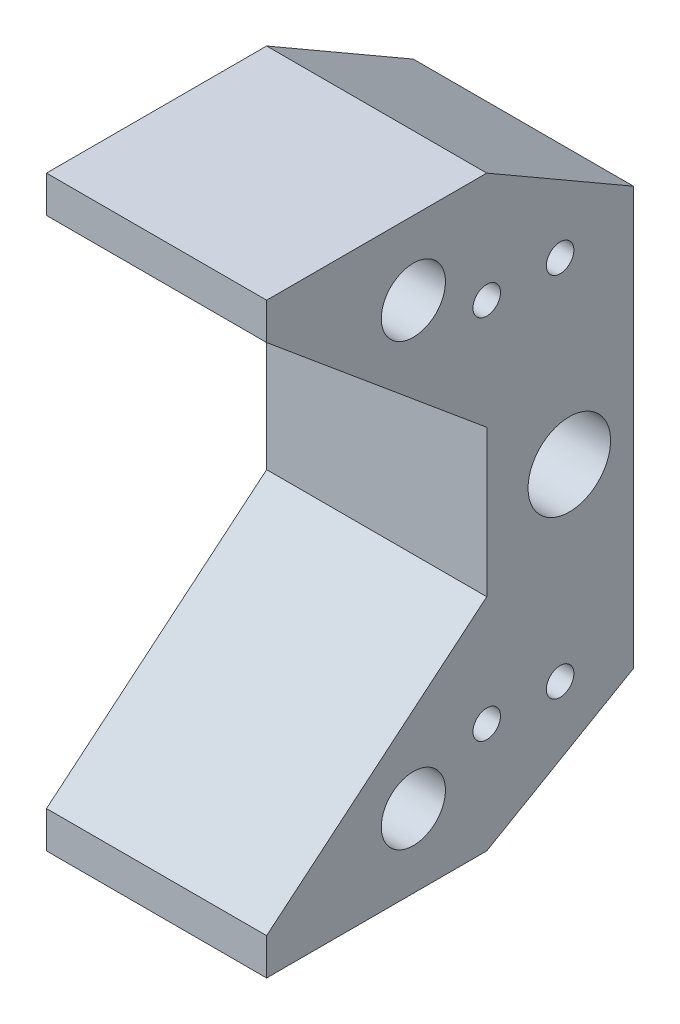
SolidWorks part; units mm, degrees
ref_plane "Front Plane" through (0, 0, 0) normal (1, 0, 0) x (0, 1, 0)
ref_plane "Top Plane" through (0, 0, 0) normal (0, 0, 1) x (0, 1, 0)
ref_plane "Right Plane" through (0, 0, 0) normal (0, 1, 0) x (-1, 0, 0)
sketch "Sketch1" plane through (0, 0, 0) normal (1, 0, 0) x (0, 1, 0)
  line L0 (0, 0) -> (-25.4, 0)
  line L1 (-25.4, 0) -> (-88.9, 76.2)
  line L2 (-88.9, 76.2) -> (-101.6, 76.2)
  line L3 (-101.6, 76.2) -> (-101.6, 0)
  line L4 (-101.6, 0) -> (-72.2706, -50.8)
  line L5 (-72.2706, -50.8) -> (0, -50.8)
  line L6 (0, -50.8) -> (0, 0)
  line L7 (-63.5, 0) -> (-63.5, -25.4) construction
  circle A0 centre (0, -28.575) radius 14.2875
  circle A1 centre (-76.2, 25.4) radius 11.1125
  circle A2 centre (-63.5, 0) radius 4.7625
  circle A3 centre (-63.5, -25.4) radius 4.7625
  point P16 (0, 0)
  dimension "D9" = 28.575
  dimension "D10" = 9.525
  dimension "D11" = 9.525
  dimension "D12" = 22.225
  dimension "D1" = 60
  dimension "D2" = 50.8
  dimension "D3" = 127
  dimension "D4" = 101.6
  dimension "D5" = 25.4
  dimension "D6" = 12.7
  dimension "D7" = 28.575
  dimension "D8" = 22.225
  dimension "D13" = 50.8
  dimension "D14" = 25.4
  dimension "D15" = 25.4
  dimension "D16" = 25.4
  dimension "D17" = 12.7
extrude "Boss-Extrude3" add sketch "Sketch1" along normal blind 76.2
mirror "Mirror1" about plane through (76.2, 0, 0) normal (0, -1, 0) of bodies 103
